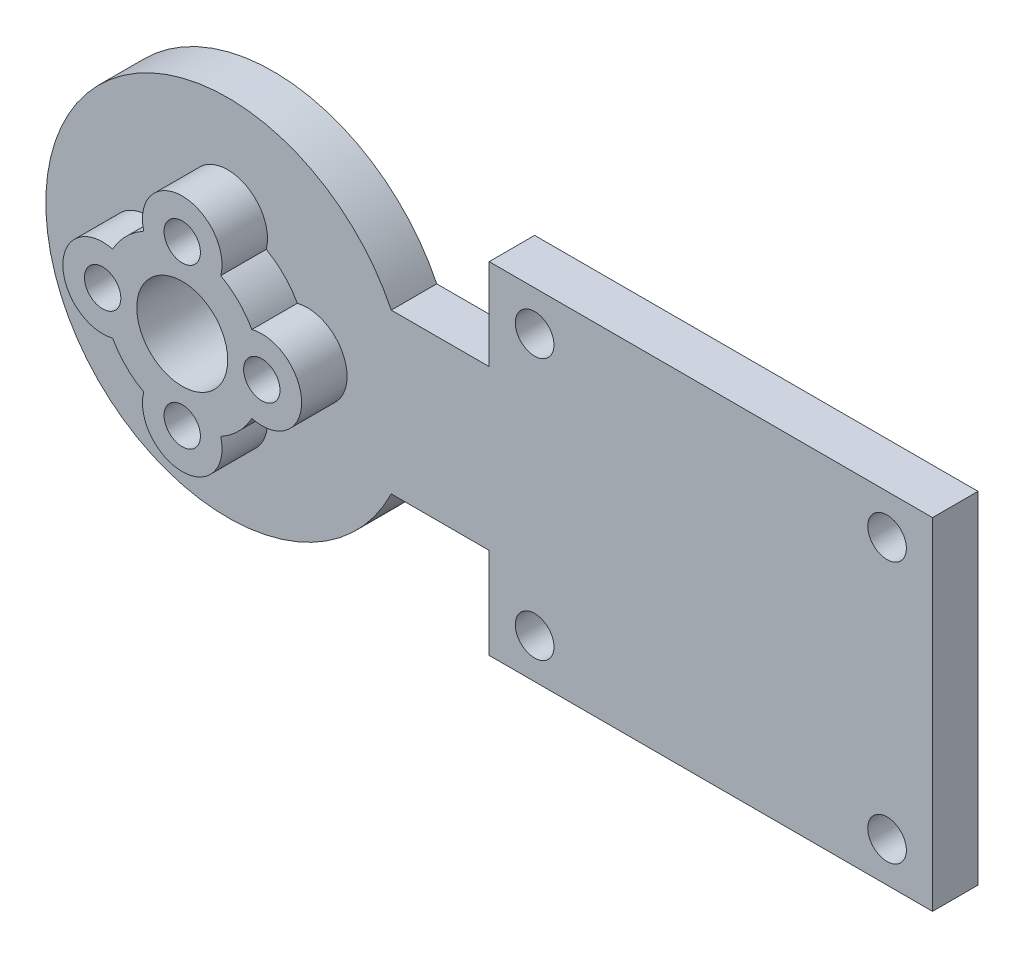
SolidWorks part; units mm, degrees
ref_plane "Front Plane" through (0, 0, 0) normal (0, 0, 1) x (1, 0, 0)
ref_plane "Top Plane" through (0, 0, 0) normal (0, 1, 0) x (1, 0, 0)
ref_plane "Right Plane" through (0, 0, 0) normal (1, 0, 0) x (0, 0, -1)
sketch "Metal_horn_flange_profile" plane through (0, 0, 0) normal (0, 0, 1) x (1, 0, 0)
  circle A0 centre (0, 0) radius 16
  dimension "D1" = 32
extrude "Metal_horn_flange" add sketch "Metal_horn_flange_profile" along normal blind 4
sketch "Straight_forearm_web_profile" plane through (0, 0, 0) normal (0, 0, 1) x (1, 0, 0)
  line L1 (0, -7) -> (28, -7)
  line L2 (0, -7) -> (0, 7)
  line L3 (0, 7) -> (28, 7)
  line L4 (28, -7) -> (28, 7)
  dimension "D1" = 28
  dimension "D2" = 14
  dimension "D3" = 7
extrude "Straight_forearm_web" add sketch "Straight_forearm_web_profile" along normal blind 4
sketch "Replaceable_tool_mounting_deck_profile" plane through (0, 0, 0) normal (0, 0, 1) x (1, 0, 0)
  line L1 (23, -15) -> (62, -15)
  line L2 (23, -15) -> (23, 15)
  line L3 (23, 15) -> (62, 15)
  line L4 (62, -15) -> (62, 15)
  dimension "D1" = 39
  dimension "D2" = 30
  dimension "D3" = 23
  dimension "D4" = 15
extrude "Replaceable_tool_mounting_deck" add sketch "Replaceable_tool_mounting_deck_profile" along normal blind 4
sketch "Dowel_support_hub_profile" plane through (0, 0, 0) normal (0, 0, 1) x (1, 0, 0)
  circle A0 centre (0, 0) radius 7
  circle A1 centre (0, 0) radius 4
  dimension "D1" = 14
  dimension "D2" = 8
extrude "Dowel_support_hub" add sketch "Dowel_support_hub_profile" along normal blind 4 from offset 4
sketch "Raised_washer_seats_PCD14" plane through (0, 0, 0) normal (0, 0, 1) x (1, 0, 0)
  circle A0 centre (7, 0) radius 3.5
  circle A1 centre (-7, 0) radius 3.5
  circle A2 centre (0, 7) radius 3.5
  circle A3 centre (0, -7) radius 3.5
  dimension "D1" = 7
  dimension "D2" = 7
  dimension "D3" = 7
  dimension "D4" = 7
  dimension "D5" = 7
  dimension "D6" = 7
  dimension "D7" = 7
  dimension "D8" = 7
extrude "Washer_seats_clear_dowel_sleeve" add sketch "Raised_washer_seats_PCD14" along normal blind 4 from offset 4
sketch "Metal_horn_M3_pattern_profile" plane through (0, 0, 0) normal (0, 0, 1) x (1, 0, 0)
  circle A0 centre (7, 0) radius 1.6
  circle A1 centre (-7, 0) radius 1.6
  circle A2 centre (0, 7) radius 1.6
  circle A3 centre (0, -7) radius 1.6
  dimension "D1" = 3.2
  dimension "D2" = 3.2
  dimension "D3" = 3.2
  dimension "D4" = 3.2
  dimension "D5" = 7
  dimension "D6" = 7
  dimension "D7" = 7
  dimension "D8" = 7
extrude "Metal_horn_M3_pattern" cut sketch "Metal_horn_M3_pattern_profile" along normal through all from offset 50
sketch "Elbow_sleeve_bore_profile" plane through (0, 0, 0) normal (0, 0, 1) x (1, 0, 0)
  circle A0 centre (0, 0) radius 4
  dimension "D1" = 8
extrude "Elbow_sleeve_bore" cut sketch "Elbow_sleeve_bore_profile" along normal through all from offset 50
sketch "Modular_tool_four_M3_pattern_profile" plane through (0, 0, 0) normal (0, 0, 1) x (1, 0, 0)
  circle A0 centre (27, -11.5) radius 1.7
  circle A1 centre (27, 11.5) radius 1.7
  circle A2 centre (58, -11.5) radius 1.7
  circle A3 centre (58, 11.5) radius 1.7
  dimension "D1" = 3.4
  dimension "D2" = 3.4
  dimension "D3" = 3.4
  dimension "D4" = 3.4
  dimension "D5" = 27
  dimension "D6" = 58
  dimension "D7" = 11.5
  dimension "D8" = 11.5
extrude "Modular_tool_four_M3_pattern" cut sketch "Modular_tool_four_M3_pattern_profile" along normal through all from offset 50
